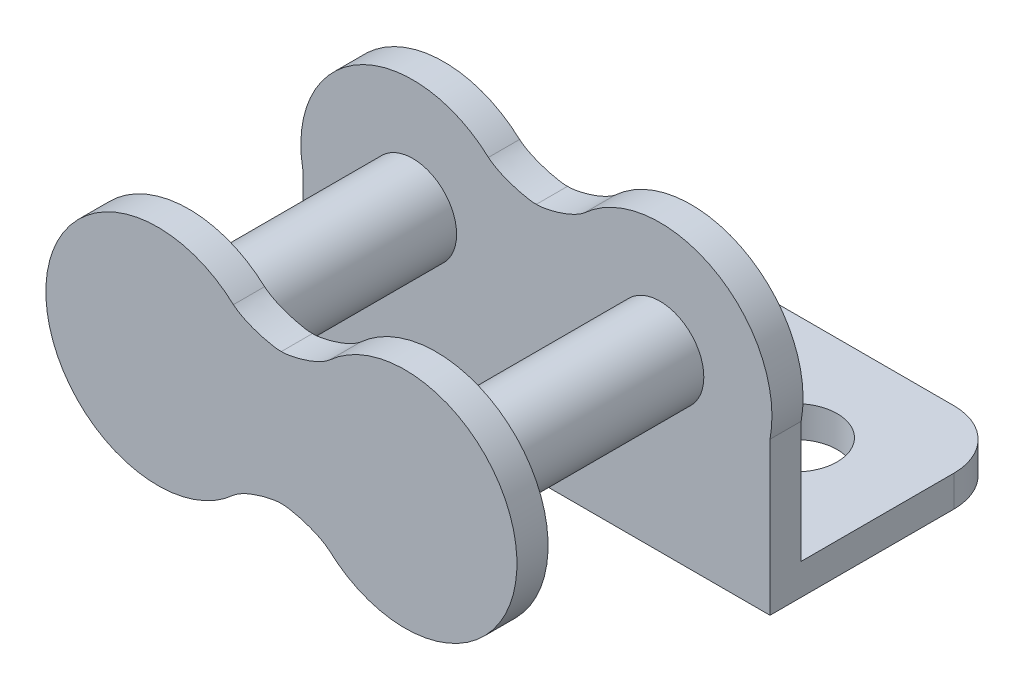
SolidWorks part; units mm, degrees
ref_plane "前视基准面" through (0, 0, 0) normal (0, 0, 1) x (1, 0, 0)
ref_plane "上视基准面" through (0, 0, 0) normal (0, 1, 0) x (1, 0, 0)
ref_plane "右视基准面" through (0, 0, 0) normal (1, 0, 0) x (0, 0, -1)
sketch "草图1" plane through (0, 0, 0) normal (0, 0, 1) x (1, 0, 0)
  line L0 (-6.35, 0) -> (66.7351, 0) construction
  line L1 (0, 69.5952) -> (0, 0) construction
  circle A0 centre (-6.35, 0) radius 4.25
  circle A1 centre (-6.35, 0) radius 2.25
  circle A2 centre (6.35, 0) radius 2.25
  circle A3 centre (6.35, 0) radius 4.25
  dimension "D1" = 4.5
  dimension "D2" = 8.5
  dimension "D3" = 12.7
extrude "凸台-拉伸1" add sketch "草图1" along normal blind 4.45
sketch "草图2" plane through (0, 0, 4.45) normal (0, 0, 1) x (1, 0, 0)
  line L0 (0, 35.0813) -> (0, 0) construction
  line L1 (-6.35, 0) -> (6.35, 0) construction
  circle A0 centre (-6.35, 0) radius 5.75
  circle A1 centre (6.35, 0) radius 5.75
  circle A2 centre (-6.35, 0) radius 2.25 construction
  circle A3 centre (-6.35, 0) radius 2.25
  circle A4 centre (6.35, 0) radius 2.25 construction
  circle A5 centre (6.35, 0) radius 2.25
  spline S0 degree 3 poles (-2.4645, 4.2386) (-1.8011, 3.6779) (-0.3708, 3.3459) (0, 3.3864) knots 0 0 0 0 1 1 1 1
  spline S1 degree 3 poles (2.4645, 4.2386) (1.8011, 3.6779) (0.3708, 3.3459) (0, 3.3864) knots 0 0 0 0 1 1 1 1
  spline S2 degree 3 poles (2.4645, -4.2386) (1.8011, -3.6779) (0.3708, -3.3459) (0, -3.3864) knots 0 0 0 0 1 1 1 1
  spline S3 degree 3 poles (-2.4645, -4.2386) (-1.8011, -3.6779) (-0.3708, -3.3459) (0, -3.3864) knots 0 0 0 0 1 1 1 1
  circle M5 centre (-6.35, 0) radius 4.25
  circle M6 centre (-6.35, 0) radius 2.25
  dimension "D1" = 11.5
extrude "凸台-拉伸3" add sketch "草图2" along normal blind 1.6 contours M5 M6 | A0 M5 | A0 S3 S2 A1 S1 S0 | A1 A5
ref_plane "基准面1" through (0, 0, 0) normal (0, 0, -1) x (-1, 0, 0)
sketch "草图3" plane through (0, 0, 0) normal (0, 0, -1) x (-1, 0, 0)
  circle A1 centre (6.35, 0) radius 4.25
  circle A2 centre (6.35, 0) radius 4.25
  circle A3 centre (-6.35, 0) radius 4.25
  circle A4 centre (-6.35, 0) radius 4.25
  dimension "D1" = 0
  dimension "D2" = 0
extrude "切除-拉伸1" cut sketch "草图3" against normal up to surface (4.45 mm away) up to face at (0, 0, 4.45)
sketch "草图4" plane through (0, 0, 6.05) normal (0, 0, 1) x (1, 0, 0)
  circle A0 centre (-6.35, 0) radius 2.25 construction
  circle A1 centre (-6.35, 0) radius 2.25
  circle A2 centre (6.35, 0) radius 2.25 construction
  circle A3 centre (6.35, 0) radius 2.25
extrude "凸台-拉伸4" add sketch "草图4" against normal blind 13.1
sketch "草图5" plane through (0, 0, -7.05) normal (0, 0, -1) x (-1, 0, 0)
  line L0 (-12.1, 0) -> (12.1, 0) construction
  line L2 (-12, -1.0677) -> (12, -1.0677)
  line L3 (-12, -1.0677) -> (-12, -8.9)
  line L4 (-12, -8.9) -> (12, -8.9)
  line L5 (12, -1.0677) -> (12, -8.9)
  arc A2 (2.4645, -4.2386) -> (2.4645, 4.2386) centre (6.35, 0) ccw
  arc A3 (-2.4645, 4.2386) -> (-2.4645, -4.2386) centre (-6.35, 0) ccw
  arc A4 (2.4645, -4.2386) -> (2.4645, 4.2386) centre (6.35, 0) ccw
  arc A5 (-2.4645, 4.2386) -> (-2.4645, -4.2386) centre (-6.35, 0) ccw
  spline S4 degree 3 poles (-2995.2472, -101.5048) (3038.5051, 205.8117) (-3029.5775, -278.8438) (2979.6155, 350.0123) knots -11.419973 -11.419973 -11.419973 -11.419973 12.235761 12.235761 12.235761 12.235761 only from (2.4645, 4.2386) to (0, 3.3864)
  spline S5 degree 3 poles (-2979.6562, 350.0165) (3029.6147, -278.847) (-3038.5385, 205.814) (2995.2766, -101.5063) knots -11.235814 -11.235814 -11.235814 -11.235814 12.420011 12.420011 12.420011 12.420011 only from (0, 3.3864) to (-2.4645, 4.2386)
  spline S6 degree 3 poles (2995.2472, 101.5048) (-3038.5051, -205.8117) (3029.5775, 278.8438) (-2979.6155, -350.0123) knots -11.419973 -11.419973 -11.419973 -11.419973 12.235761 12.235761 12.235761 12.235761 only from (-2.4645, -4.2386) to (0, -3.3864)
  spline S7 degree 3 poles (2979.6562, -350.0165) (-3029.6147, 278.847) (3038.5385, -205.814) (-2995.2766, 101.5063) knots -11.235814 -11.235814 -11.235814 -11.235814 12.420011 12.420011 12.420011 12.420011 only from (0, -3.3864) to (2.4645, -4.2386)
  spline S8 degree 3 poles (2.4645, 4.2386) (1.8011, 3.6779) (0.3708, 3.3459) (0, 3.3864) knots 0 0 0 0 1 1 1 1
  spline S9 degree 3 poles (0, 3.3864) (-0.3708, 3.3459) (-1.8011, 3.6779) (-2.4645, 4.2386) knots 0 0 0 0 1 1 1 1
  spline S10 degree 3 poles (-2.4645, -4.2386) (-1.8011, -3.6779) (-0.3708, -3.3459) (0, -3.3864) knots 0 0 0 0 1 1 1 1
  spline S11 degree 3 poles (0, -3.3864) (0.3708, -3.3459) (1.8011, -3.6779) (2.4645, -4.2386) knots 0 0 0 0 1 1 1 1
  circle M12 centre (6.35, 0) radius 2.25
  dimension "D2" = 24
  dimension "D3" = 8.9
  dimension "D1" = 0
extrude "凸台-拉伸6" add sketch "草图5" along normal blind 1.6 contours A5 L0 A4 S8 S9 M12 | L0 A5 L2 M12 | S11 S10 A5 L3 L4 L5 A4 | S10 S11 A4 L2 A5 M12 | L0 L2 A4 M12 | L0 L2 M12 | L2 M12 | L0 M12
sketch "草图6" plane through (0, 0, -8.65) normal (0, 0, -1) x (-1, 0, 0)
  line L0 (-12, -1.0677) -> (-12, -8.9) construction
  line L1 (12, -8.9) -> (-12, -8.9)
  line L2 (12, -8.9) -> (12, -7.3)
  line L3 (12, -7.3) -> (-12, -7.3)
  line L4 (-12, -8.9) -> (-12, -7.3)
  dimension "D1" = 1.6
extrude "凸台-拉伸7" add sketch "草图6" along normal blind 10.85
ref_plane "基准面4" through (0, 0, -1.3) normal (0, 0, -1) x (-1, 0, 0)
sketch "草图9" plane through (0, -8.9, 0) normal (0, -1, 0) x (1, 0, 0)
  line L0 (-12, -14) -> (12, -14) construction
  line L1 (-12, -19.5) -> (-12, -7.05) construction
  line L2 (12, -19.5) -> (12, -7.05) construction
  line L4 (0, -19.5) -> (0, -7.05) construction
  line L5 (12, -19.5) -> (-12, -19.5) construction
  line L6 (12, -7.05) -> (-12, -7.05) construction
  circle A0 centre (-6.35, -14) radius 2.15
  circle A1 centre (6.35, -14) radius 2.15
  dimension "D1" = 4.3
  dimension "D2" = 12.7
  dimension "D3" = 5.5
extrude "切除-拉伸2" cut sketch "草图9" against normal through all
fillet "圆角1" radius 3 2 edges at (12, -8.1, -19.5) (-12, -8.1, -19.5)
